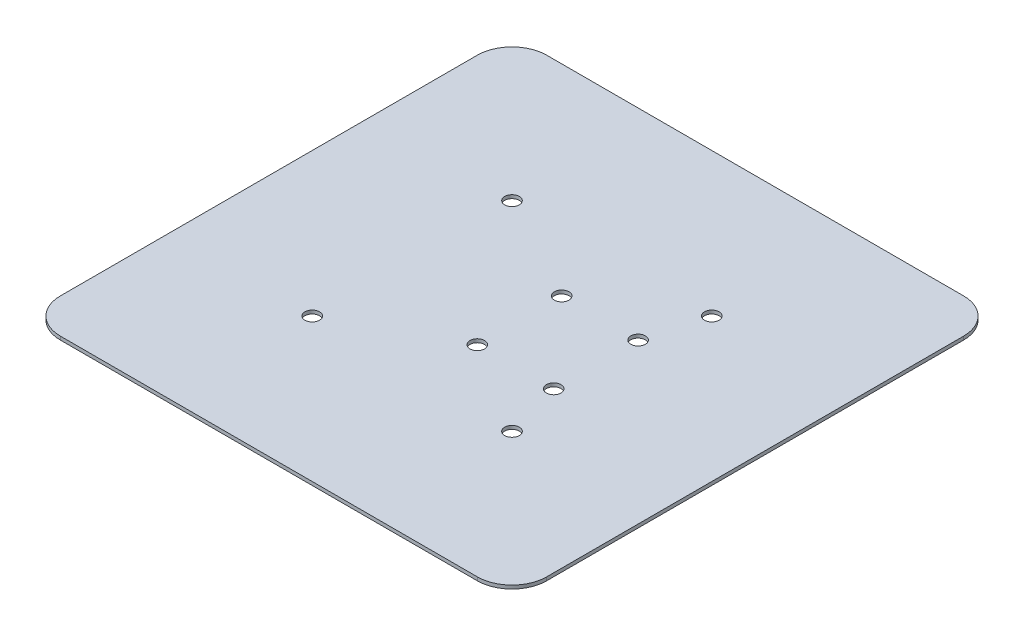
SolidWorks part; units mm, degrees
ref_plane "Front Plane" through (0, 0, 0) normal (0, 0, 1) x (1, 0, 0)
ref_plane "Top Plane" through (0, 0, 0) normal (0, 1, 0) x (1, 0, 0)
ref_plane "Right Plane" through (0, 0, 0) normal (1, 0, 0) x (0, 0, -1)
sketch "Sketch1" plane through (0, 0, 0) normal (0, 1, 0) x (1, 0, 0)
  line L1 (0, 0) -> (140, 0)
  line L2 (0, 0) -> (0, -140)
  line L3 (0, -140) -> (140, -140)
  line L4 (140, 0) -> (140, -140)
  dimension "D1" = 140
  dimension "D2" = 140
extrude "Boss-Extrude1" add sketch "Sketch1" along normal blind 1
fillet "Fillet1" radius 10 4 edges at (140, 0.5, 0) (0, 0.5, 0) (0, 0.5, 140) (140, 0.5, 140)
sketch "Sketch2" plane through (0, 1, 0) normal (0, 1, 0) x (1, 0, 0)
  line L0 (10, -140) -> (130, -140) construction
  line L1 (140, -130) -> (140, -10) construction
  line L3 (130, 0) -> (10, 0) construction
  circle A0 centre (98.75, -98.75) radius 2.1
  circle A1 centre (41.25, -98.75) radius 2.1
  circle A2 centre (41.25, -41.25) radius 2.1
  circle A3 centre (98.75, -41.25) radius 2.1
  circle A4 centre (72.15, -57.85) radius 2.1
  circle A5 centre (94.15, -57.85) radius 2.1
  circle A6 centre (72.15, -82.15) radius 2.1
  circle A7 centre (94.15, -82.15) radius 2.1
  dimension "D1" = 4.2
  dimension "D6" = 4.2
  dimension "D2" = 41.25
  dimension "D3" = 41.25
  dimension "D4" = 57.5
  dimension "D5" = 41.25
  dimension "D7" = 22
  dimension "D8" = 24.3
  dimension "D9" = 57.85
  dimension "D10" = 45.85
extrude "Cut-Extrude1" cut sketch "Sketch2" against normal blind 10
